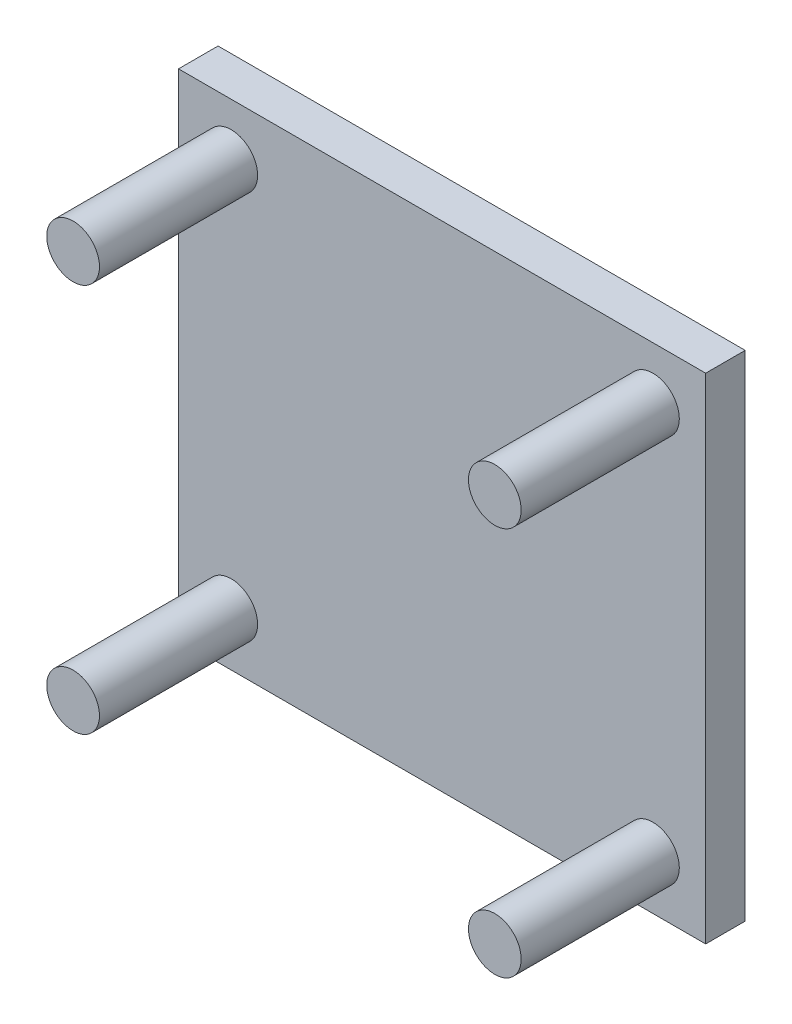
SolidWorks part; units mm, degrees
ref_plane "Спереди" through (0, 0, 0) normal (0, 0, 1) x (1, 0, 0)
ref_plane "Сверху" through (0, 0, 0) normal (0, 1, 0) x (1, 0, 0)
ref_plane "Справа" through (0, 0, 0) normal (1, 0, 0) x (0, 0, -1)
sketch "Эскиз1" plane through (0, 0, 0) normal (0, 0, 1) x (1, 0, 0)
  line L0 (-20, -18.7553) -> (20, -18.7553)
  line L1 (20, -18.7553) -> (20, 18.7553)
  line L2 (20, 18.7553) -> (-20, 18.7553)
  line L3 (-20, 18.7553) -> (-20, -18.7553)
extrude "Former_base" add sketch "Эскиз1" along normal blind 3
sketch "Эскиз2" plane through (0, 0, 0) normal (0, 0, 1) x (1, 0, 0)
  circle A0 centre (-16, -14.7553) radius 2
  circle A1 centre (-16, 14.7553) radius 2
  circle A2 centre (16, -14.7553) radius 2
  circle A3 centre (16, 14.7553) radius 2
extrude "Former_posts" add sketch "Эскиз2" along normal blind 12 from offset 3
